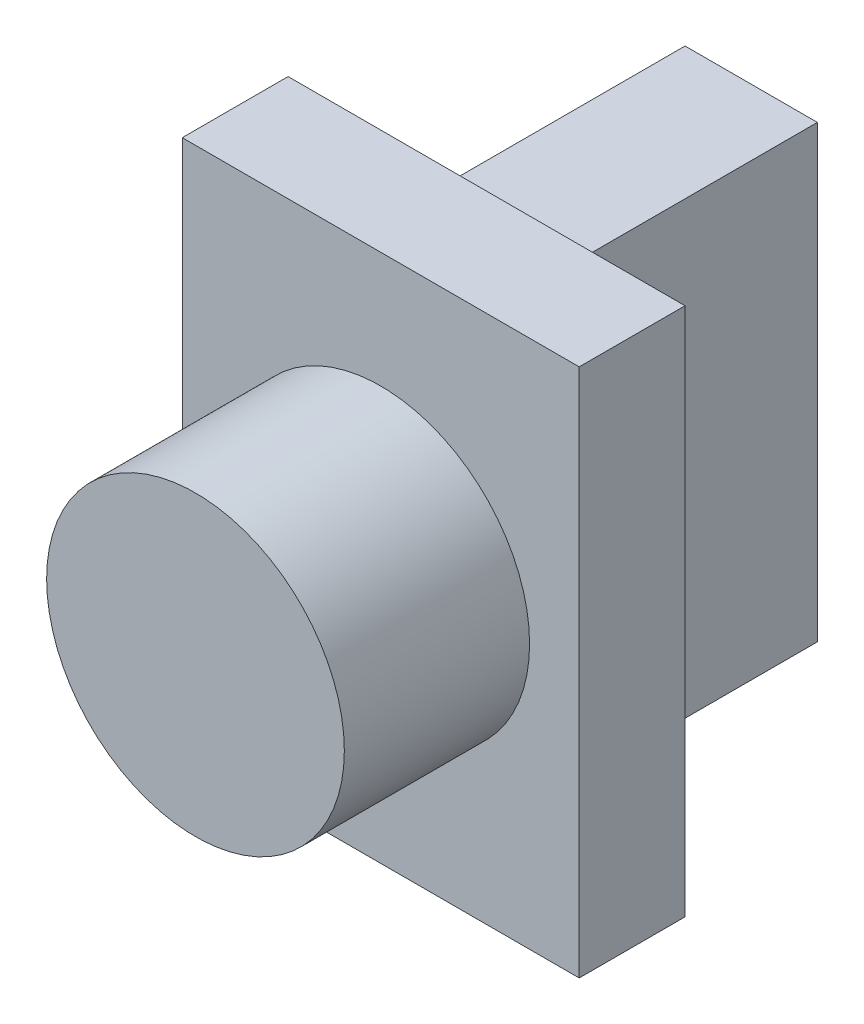
SolidWorks part; units mm, degrees
material "PW80:Mi:0:41:Ar:0:-1:C1:1:2:3:Re:15:"
ref_plane "Plan1" through (0, 0, 0) normal (0, 0, 1) x (1, 0, 0)
ref_plane "Plan2" through (0, 0, 0) normal (0, 1, 0) x (1, 0, 0)
ref_plane "Plan3" through (0, 0, 0) normal (1, 0, 0) x (0, 0, -1)
sketch "Esquisse1" plane through (0, 0, 0) normal (0, 0, 1) x (1, 0, 0)
  line L1 (-15, 20) -> (15, 20)
  line L2 (-15, 20) -> (-15, -20)
  line L3 (-15, -20) -> (15, -20)
  line L4 (15, 20) -> (15, -20)
extrude "Base-Extrusion" add sketch "Esquisse1" along normal blind 8
sketch "Esquisse2" plane through (0, 0, 0) normal (0, 0, -1) x (-1, 0, 0)
  line L1 (-5, 17) -> (5, 17)
  line L2 (-5, 17) -> (-5, -17)
  line L3 (-5, -17) -> (5, -17)
  line L4 (5, 17) -> (5, -17)
extrude "Boss.-Extru.1" add sketch "Esquisse2" along normal blind 20
sketch "Esquisse3" plane through (0, 0, 8) normal (0, 0, 1) x (1, 0, 0)
  circle A0 centre (0, 0) radius 11.25
extrude "Boss.-Extru.2" add sketch "Esquisse3" along normal blind 14
